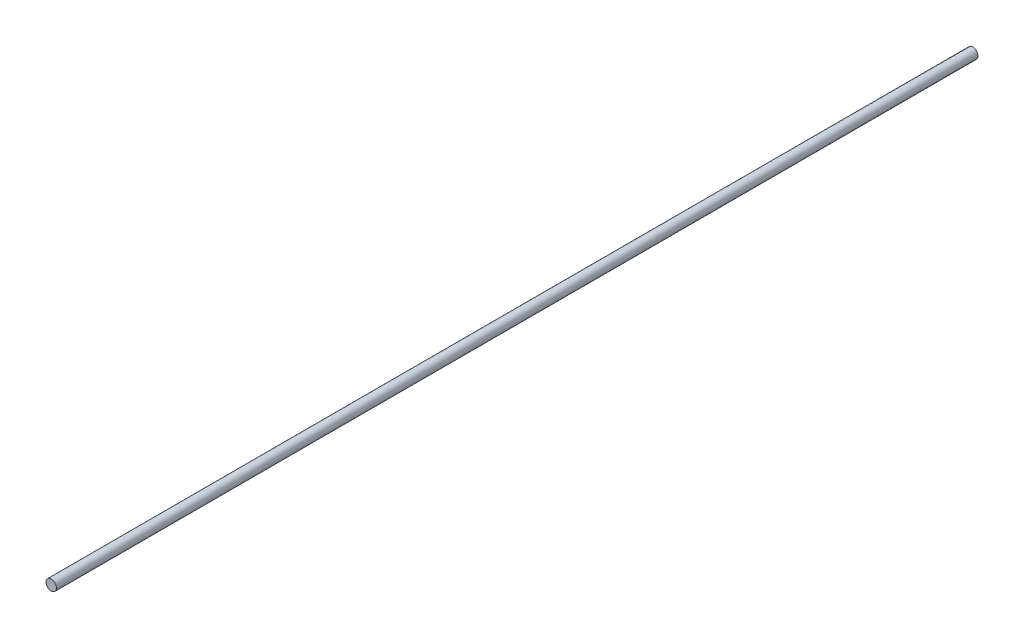
SolidWorks part; units mm, degrees
material "1060 Alloy"
ref_plane "Front Plane" through (0, 0, 0) normal (0, 0, 1) x (1, 0, 0)
ref_plane "Top Plane" through (0, 0, 0) normal (0, 1, 0) x (1, 0, 0)
ref_plane "Right Plane" through (0, 0, 0) normal (1, 0, 0) x (0, 0, -1)
sketch "Sketch1" plane through (0, 0, 0) normal (0, 0, 1) x (1, 0, 0)
  circle A0 centre (0, 0) radius 6.35
  dimension "D1" = 12.7
extrude "Boss-Extrude1" add sketch "Sketch1" along normal blind 1121.918
equation "\"A\"= 0.1963"
equation "\"def\"= .009"
equation "\"E\"= 10 * 10 ^ 6"
equation "\"F\"= 400"
equation "\"L\"= \"E\" * \"A\" * \"def\" / \"F\""
equation "\"d\"= .5"
equation "\"D1@Sketch1\"=\"d\""
